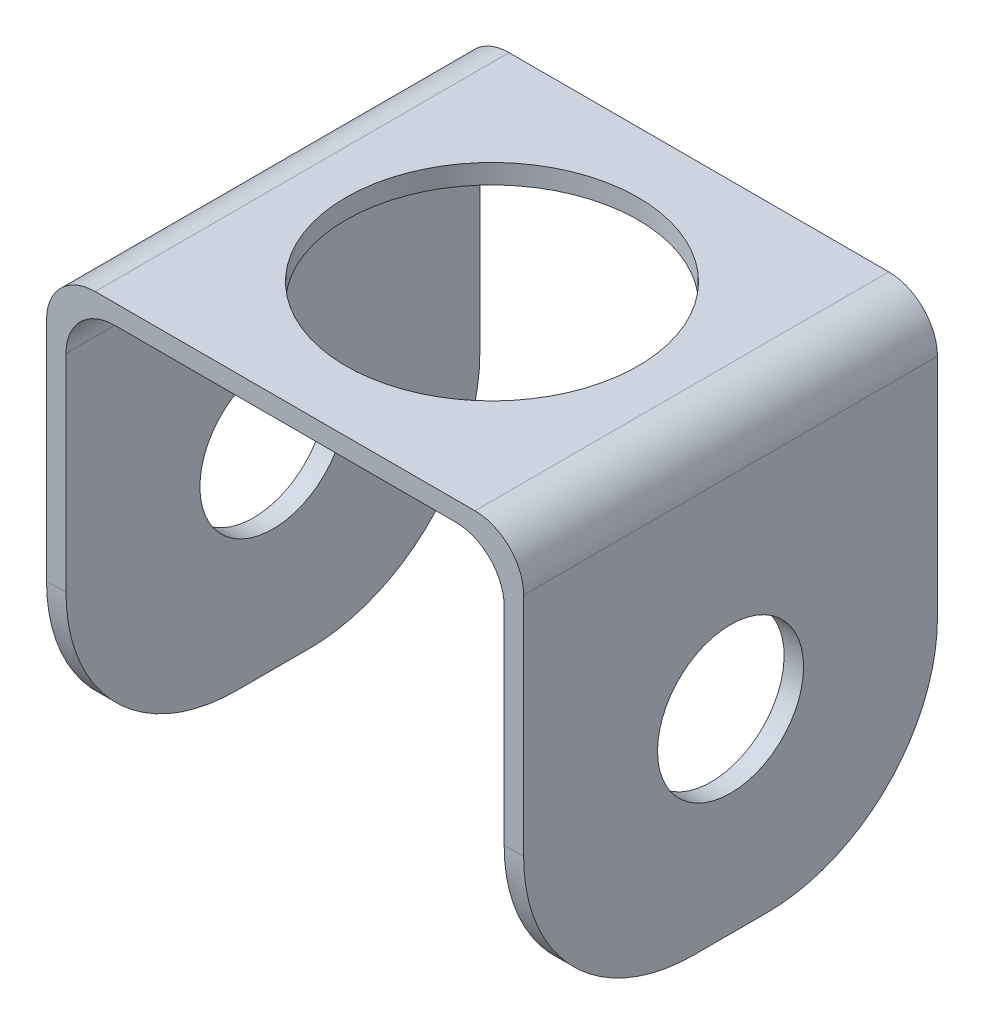
SolidWorks part; units mm, degrees
material "6061 合金"
ref_plane "前视基准面" through (0, 0, 0) normal (0, 0, 1) x (1, 0, 0)
ref_plane "上视基准面" through (0, 0, 0) normal (0, 1, 0) x (1, 0, 0)
ref_plane "右视基准面" through (0, 0, 0) normal (1, 0, 0) x (0, 0, -1)
other "Configuration Table"
sketch "草图1" plane through (0, 0, 0) normal (0, 0, 1) x (1, 0, 0)
  line L0 (-180, 0) -> (0, 0)
  line L1 (0, 0) -> (0, -175)
  line L3 (8, -175) -> (8, 8)
  line L4 (8, 8) -> (-180, 8)
  line L6 (0, -175) -> (8, -175)
  line L12 (-180, 8) -> (-188, 8)
  line L13 (-180, 0) -> (-180, -175)
  line L14 (-180, -175) -> (-188, -175)
  line L15 (-188, 8) -> (-188, -175)
  dimension "D1" = 8
  dimension "D2" = 8
  dimension "D4" = 180
  dimension "D5" = 183
  dimension "D6" = 8
  dimension "D8" = 8
extrude "凸台-拉伸1" add sketch "草图1" along normal blind 170
sketch "草图2" plane through (0, 8, 0) normal (0, 1, 0) x (1, 0, 0)
  line L0 (-216.3195, -85) -> (51.5119, -85) construction
  line L1 (8, -170) -> (-188, -170) construction
  line L2 (8, 0) -> (-188, 0) construction
  line L7 (-90, -75.3242) -> (-90, -92.2023) construction
  line L8 (8, -170) -> (8, 0) construction
  line L9 (-188, -170) -> (-188, 0) construction
  circle A2 centre (-90, -85) radius 60
  dimension "D3" = 120
extrude "切除-拉伸1" cut sketch "草图2" against normal blind 180 contours A2 L0 | L0 A2
sketch "草图3" plane through (8, 0, 0) normal (1, 0, 0) x (0, 0, -1)
  line L0 (-85, 25.6845) -> (-85, -173.3318) construction
  line L1 (0, -175) -> (0, 8) construction
  line L2 (-170, -175) -> (-170, 8) construction
  line L3 (-170, -175) -> (0, -175) construction
  line L4 (0, 0) -> (-209.686, 0) construction
  circle A0 centre (-85, -95) radius 30
  dimension "D1" = 60
  dimension "D2" = 80
extrude "切除-拉伸2" cut sketch "草图3" against normal through all both and the other way through all contours A0
fillet "圆角1" radius 70 4 edges at (-184, -175, 170) (-184, -175, 0) (4, -175, 0) (4, -175, 170)
fillet "圆角2" radius 20 2 edges at (-180, 0, 85) (0, 0, 85)
fillet "圆角3" radius 20 2 edges at (8, 8, 85) (-188, 8, 85)
